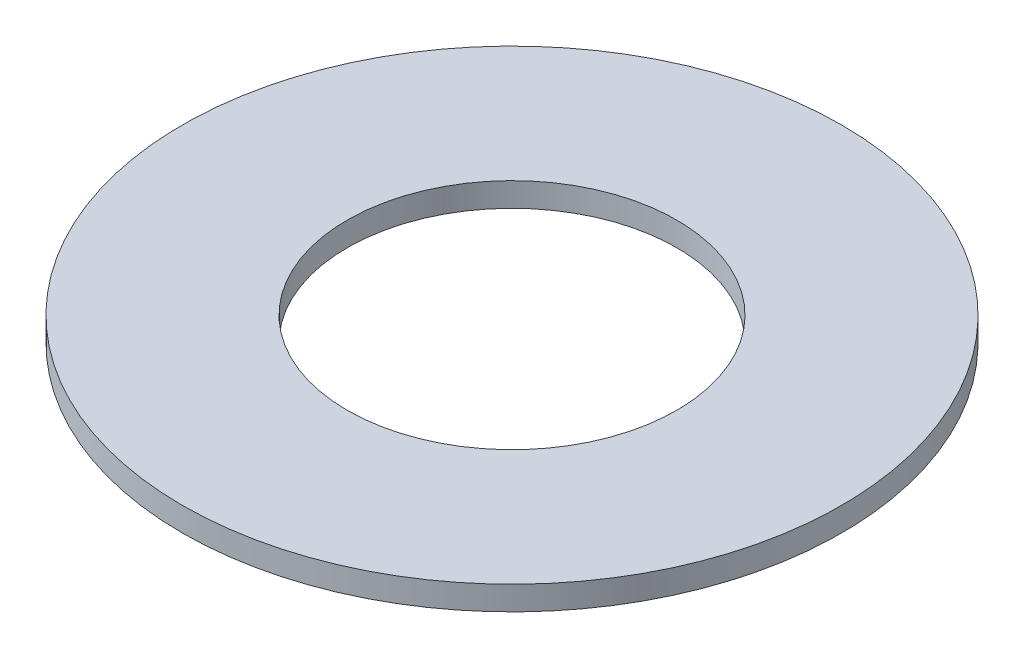
SolidWorks part; units mm, degrees
ref_plane "Front" through (0, 0, 0) normal (0, 0, 1) x (1, 0, 0)
ref_plane "Top" through (0, 0, 0) normal (0, 1, 0) x (1, 0, 0)
ref_plane "Right" through (0, 0, 0) normal (1, 0, 0) x (0, 0, -1)
sketch "Sketch1" plane through (0, 0, 0) normal (0, 1, 0) x (1, 0, 0)
  circle A0 centre (0, 0) radius 5.5
  circle A1 centre (0, 0) radius 11
  dimension "D1" = 22
  dimension "D2" = 11
extrude "Boss-Extrude1" add sketch "Sketch1" along normal blind 0.8
